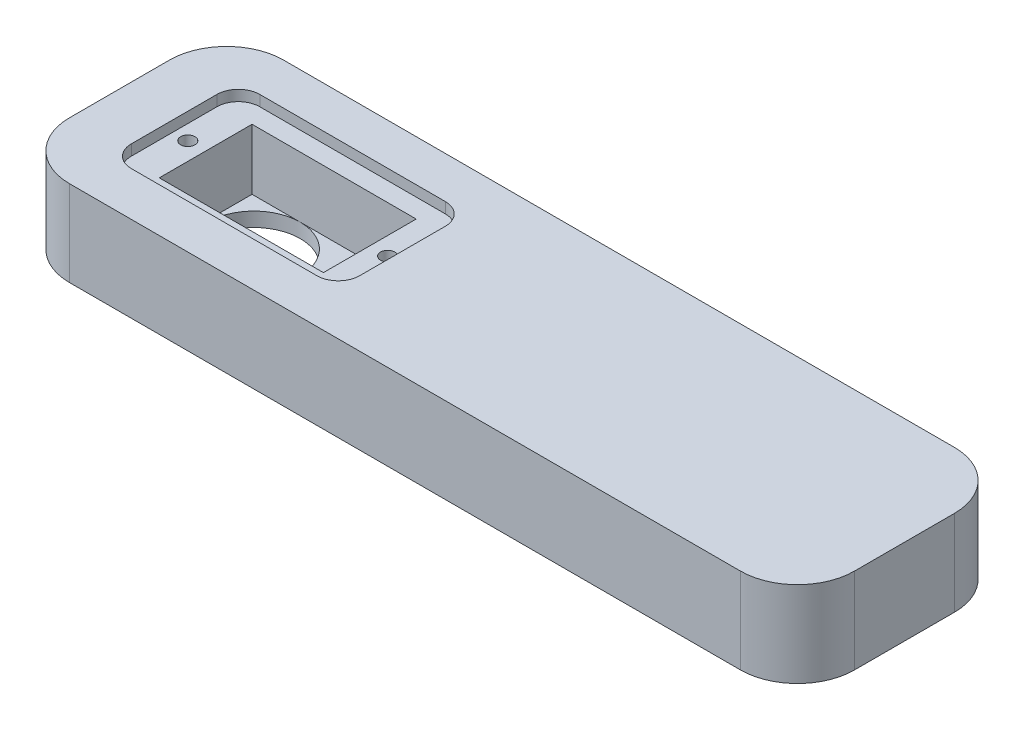
SolidWorks part; units mm, degrees
ref_plane "Front Plane" through (0, 0, 0) normal (0, 0, 1) x (1, 0, 0)
ref_plane "Top Plane" through (0, 0, 0) normal (0, 1, 0) x (1, 0, 0)
ref_plane "Right Plane" through (0, 0, 0) normal (1, 0, 0) x (0, 0, -1)
sketch "Sketch1" plane through (0, 0, 0) normal (0, 1, 0) x (1, 0, 0)
  line L1 (-46.7568, 18.1081) -> (63.2432, 18.1081)
  line L2 (-46.7568, 18.1081) -> (-46.7568, -11.8919)
  line L3 (-46.7568, -11.8919) -> (63.2432, -11.8919)
  line L4 (63.2432, 18.1081) -> (63.2432, -11.8919)
  dimension "D1" = 110
  dimension "D2" = 30
extrude "Boss-Extrude1" add sketch "Sketch1" along normal blind 12
fillet "Fillet2" radius 8 4 edges at (63.2432, 6, -18.1081) (63.2432, 6, 11.8919) (-46.7568, 6, -18.1081) (-46.7568, 6, 11.8919)
sketch "Sketch3" plane through (0, 12, 0) normal (0, 1, 0) x (1, 0, 0)
  line L0 (55.2432, 18.1081) -> (-38.7568, 18.1081) construction
  line L1 (-34.6791, 9.6081) -> (-11.6791, 9.6081)
  line L2 (-34.6791, 9.6081) -> (-34.6791, -3.3919)
  line L3 (-34.6791, -3.3919) -> (-11.6791, -3.3919)
  line L4 (-11.6791, 9.6081) -> (-11.6791, -3.3919)
  point P4 (-23.1791, 9.6081)
  dimension "D1" = 23
  dimension "D2" = 13
  dimension "D3" = 8.5
sketch "Sketch4" plane through (0, 12, 0) normal (0, 1, 0) x (1, 0, 0)
  line L0 (55.2432, 18.1081) -> (-38.7568, 18.1081) construction
  line L1 (-34.6791, 9.6081) -> (-34.6791, -3.3919) construction
  line L2 (8.2432, 18.1081) -> (8.2432, -21.5981) construction
  circle A0 centre (-27.9291, 3.1081) radius 6.5
  dimension "D1" = 15
  dimension "D2" = 6.75
extrude "Cut-Extrude1" cut sketch "Sketch4" against normal through all contours A0
extrude "Cut-Extrude2" cut sketch "Sketch3" against normal blind 10
sketch "Sketch5" plane through (0, 12, 0) normal (0, 1, 0) x (1, 0, 0)
  line L1 (-39.2623, 12.2731) -> (-7.2623, 12.2731)
  line L2 (-39.2623, 12.2731) -> (-39.2623, -5.7269)
  line L3 (-39.2623, -5.7269) -> (-7.2623, -5.7269)
  line L4 (-7.2623, 12.2731) -> (-7.2623, -5.7269)
  dimension "D1" = 32
  dimension "D2" = 18
extrude "Cut-Extrude3" cut sketch "Sketch5" against normal blind 1.5
fillet "Fillet4" radius 3 4 edges at (-39.2623, 11.25, 5.7269) (-7.2623, 11.25, 5.7269) (-39.2623, 11.25, -12.2731) (-7.2623, 11.25, -12.2731)
sketch "Sketch6" plane through (0, 10.5, 0) normal (0, 1, 0) x (1, 0, 0)
  line L0 (-34.6791, -3.3919) -> (-34.6791, 9.6081) construction
  line L1 (-23.1791, 9.6081) -> (-23.1791, 11.5535) construction
  line L2 (-34.6791, 9.6081) -> (-11.6791, 9.6081) construction
  circle A0 centre (-37.1791, 3.1081) radius 1
  circle A1 centre (-9.1791, 3.1081) radius 1
  dimension "D1" = 2.5
extrude "Cut-Extrude4" cut sketch "Sketch6" against normal blind 4
